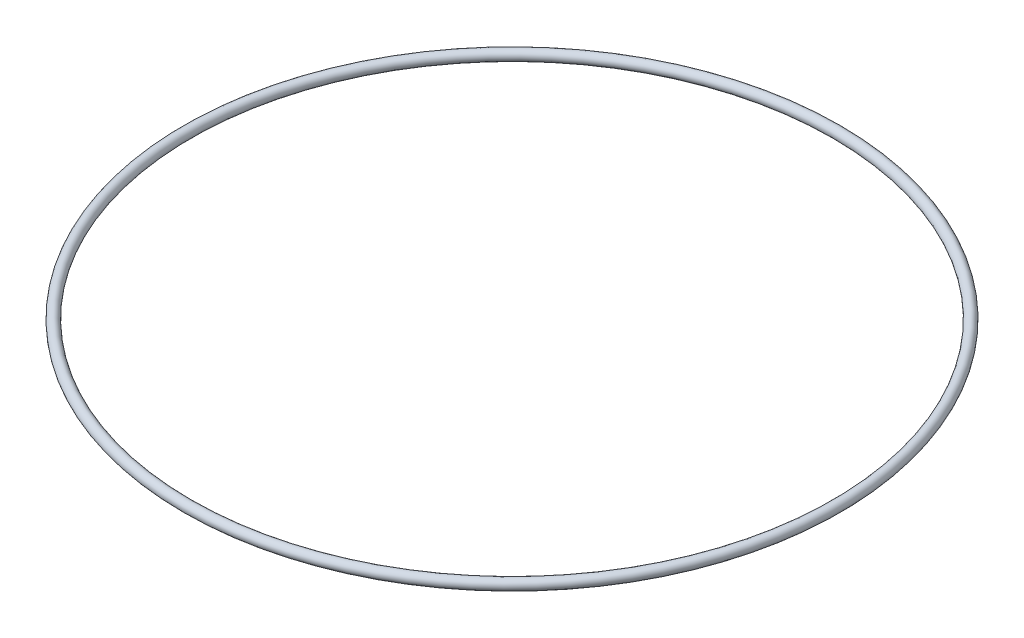
SolidWorks part; units mm, degrees
ref_plane "Płaszczyzna przednia" through (0, 0, 0) normal (0, 0, 1) x (1, 0, 0)
ref_plane "Płaszczyzna górna" through (0, 0, 0) normal (0, 1, 0) x (1, 0, 0)
ref_plane "Płaszczyzna prawa" through (0, 0, 0) normal (1, 0, 0) x (0, 0, -1)
sketch "Szkic1" plane through (0, 0, 0) normal (0, 1, 0) x (1, 0, 0)
  line L0 (0, 62.5) -> (0, -62.5) construction
  circle A0 centre (0, 0) radius 62.5
  dimension "D1" = 125
sweep "Wyciągnięcie po ścieżce1" add path "Szkic1" circular profile diameter 2 parameters "D3"=2
